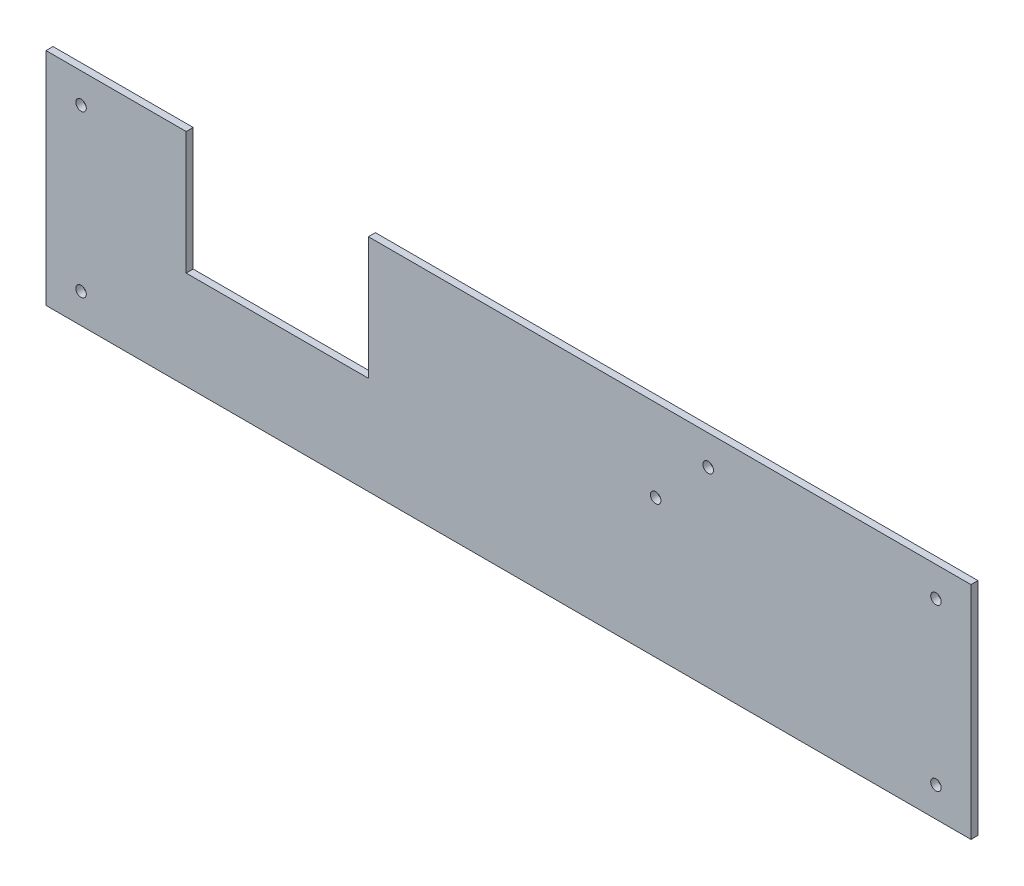
SolidWorks part; units mm, degrees
ref_plane "Plan de face" through (0, 0, 0) normal (0, 0, 1) x (1, 0, 0)
ref_plane "Plan de dessus" through (0, 0, 0) normal (0, 1, 0) x (1, 0, 0)
ref_plane "Plan de droite" through (0, 0, 0) normal (1, 0, 0) x (0, 0, -1)
sketch "Esquisse1" plane through (0, 0, 0) normal (0, 0, 1) x (1, 0, 0)
  line L1 (-45.7387, 49.9082) -> (218.2613, 49.9082)
  line L2 (-45.7387, 49.9082) -> (-45.7387, -13.0918)
  line L3 (-45.7387, -13.0918) -> (218.2613, -13.0918)
  line L4 (218.2613, 49.9082) -> (218.2613, -13.0918)
  circle A0 centre (-35.7387, 41.4082) radius 1.5
  circle A1 centre (-35.7387, -4.5918) radius 1.5
  circle A2 centre (208.2613, 41.4082) radius 1.5
  circle A3 centre (208.2613, -4.5918) radius 1.5
  dimension "D3" = 8.5
  dimension "D5" = 8.5
  dimension "D7" = 10
  dimension "D1" = 63
  dimension "D2" = 264
  dimension "D4" = 10
  dimension "D6" = 10
  dimension "D8" = 8.5
  dimension "D9" = 10
  dimension "D10" = 8.5
extrude "Extrusion1" add sketch "Esquisse1" along normal blind 2
sketch "Esquisse2" plane through (0, 0, 2) normal (0, 0, 1) x (1, 0, 0)
  line L0 (218.2613, 49.9082) -> (-45.7387, 49.9082) construction
  line L1 (218.2613, -13.0918) -> (218.2613, 49.9082) construction
  circle A0 centre (143.2613, 41.4082) radius 1.5
  circle A1 centre (128.2613, 26.4082) radius 1.5
  dimension "D1" = 8.5
  dimension "D3" = 23.5
  dimension "D2" = 75
  dimension "D4" = 90
extrude "Extrusion2" cut sketch "Esquisse2" against normal blind 10
sketch "Esquisse3" plane through (0, 0, 2) normal (0, 0, 1) x (1, 0, 0)
  line L0 (218.2613, 49.9082) -> (-45.7387, 49.9082) construction
  line L1 (-5.7387, 49.9082) -> (46.2613, 49.9082)
  line L2 (-5.7387, 49.9082) -> (-5.7387, 14.9082)
  line L3 (-5.7387, 14.9082) -> (46.2613, 14.9082)
  line L4 (46.2613, 49.9082) -> (46.2613, 14.9082)
  line L5 (-45.7387, 49.9082) -> (-45.7387, -13.0918) construction
  dimension "D1" = 52
  dimension "D2" = 35
  dimension "D3" = 40
extrude "Extrusion3" cut sketch "Esquisse3" against normal blind 10
